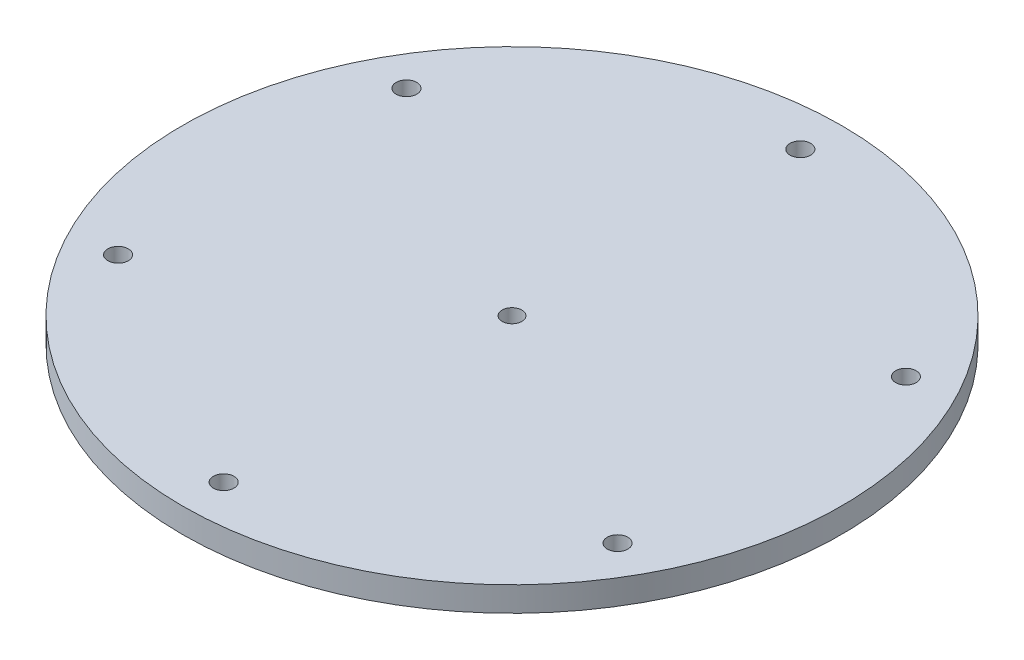
SolidWorks part; units mm, degrees
ref_plane "Front Plane" through (0, 0, 0) normal (0, 0, 1) x (1, 0, 0)
ref_plane "Top Plane" through (0, 0, 0) normal (0, 1, 0) x (1, 0, 0)
ref_plane "Right Plane" through (0, 0, 0) normal (1, 0, 0) x (0, 0, -1)
sketch "Sketch1" plane through (0, 0, 0) normal (0, 1, 0) x (1, 0, 0)
  circle A0 centre (0, 0) radius 80
  circle A1 centre (0, 0) radius 70 construction
  circle A2 centre (0, 70) radius 2.5
  circle A3 centre (60.6218, 35) radius 2.5
  circle A4 centre (60.6218, -35) radius 2.5
  circle A5 centre (0, -70) radius 2.5
  circle A6 centre (-60.6218, -35) radius 2.5
  circle A7 centre (-60.6218, 35) radius 2.5
  circle A8 centre (0, 0) radius 2.4
  point P18 (0, 0)
  dimension "D1" = 6
extrude "Boss-Extrude1" add sketch "Sketch1" along normal blind 6
